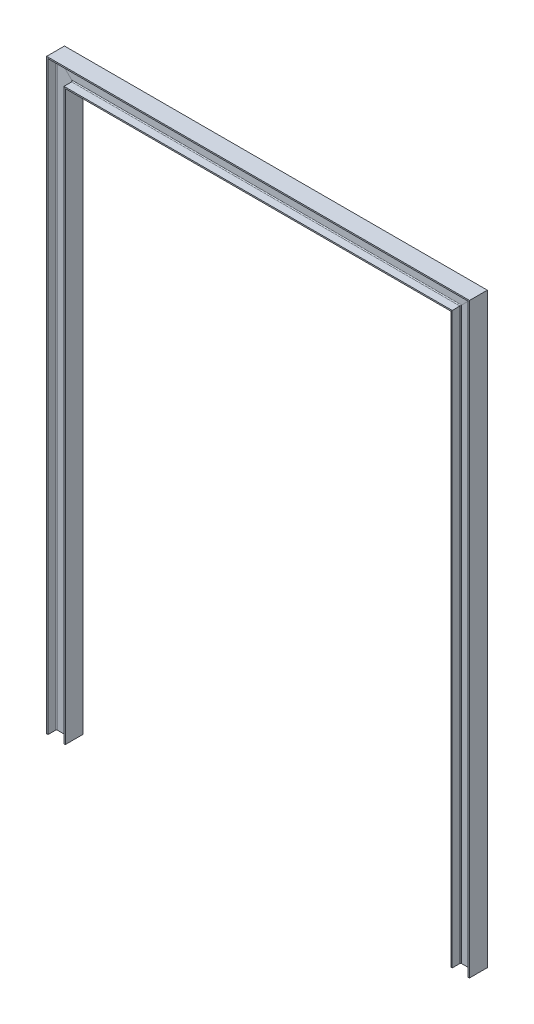
SolidWorks part; units mm, degrees
material "ASTM A36 Steel"
ref_plane "Front Plane" through (0, 0, 0) normal (0, 0, 1) x (1, 0, 0)
ref_plane "Top Plane" through (0, 0, 0) normal (0, 1, 0) x (1, 0, 0)
ref_plane "Right Plane" through (0, 0, 0) normal (1, 0, 0) x (0, 0, -1)
sketch "Sketch1" plane through (0, 0, 0) normal (0, 0, 1) x (1, 0, 0)
  line L0 (0, 0) -> (0, 10000)
  line L1 (0, 10000) -> (7000, 10000)
  line L2 (7000, 10000) -> (7000, 0)
  dimension "D1" = 10000
  dimension "D2" = 7000
other "W section W12X96(1)"
ref_plane "Plane1" through (0, 0, 0) normal (0, 1, 0) x (0, 0, 1)
sketch "Sketch13" plane through (0, 0, 0) normal (0, 1, 0) x (0, 0, 1)
  line L0 (-154.432, -161.417) -> (-154.432, -138.557)
  line L1 (-154.432, -138.557) -> (-22.225, -138.557)
  line L2 (-6.985, -123.317) -> (-6.985, 123.317)
  line L3 (-22.225, 138.557) -> (-154.432, 138.557)
  line L4 (-154.432, 138.557) -> (-154.432, 161.417)
  line L5 (-154.432, 161.417) -> (154.432, 161.417)
  line L6 (154.432, 161.417) -> (154.432, 138.557)
  line L7 (154.432, 138.557) -> (22.225, 138.557)
  line L8 (6.985, 123.317) -> (6.985, -123.317)
  line L9 (22.225, -138.557) -> (154.432, -138.557)
  line L10 (154.432, -138.557) -> (154.432, -161.417)
  line L11 (154.432, -161.417) -> (-154.432, -161.417)
  line L12 (0, 0) -> (0, 161.417) construction
  line L13 (-6.985, 0) -> (6.985, 0) construction
  arc A0 (-22.225, -138.557) -> (-6.985, -123.317) centre (-22.225, -123.317) ccw
  arc A1 (-6.985, 123.317) -> (-22.225, 138.557) centre (-22.225, 123.317) ccw
  arc A2 (22.225, 138.557) -> (6.985, 123.317) centre (22.225, 123.317) ccw
  arc A3 (6.985, -123.317) -> (22.225, -138.557) centre (22.225, -123.317) ccw
  point P23 (-154.432, 0)
  point P26 (0, -161.417)
  point P27 (154.432, 0)
  point P28 (0, 0)
  dimension "Ri" = 15.24
  dimension "D1" = 6.985
  dimension "D2" = 22.86
  dimension "Tw" = 13.97
  dimension "Bf" = 308.864
  dimension "Depth" = 322.834
  dimension "Tf" = 22.86
